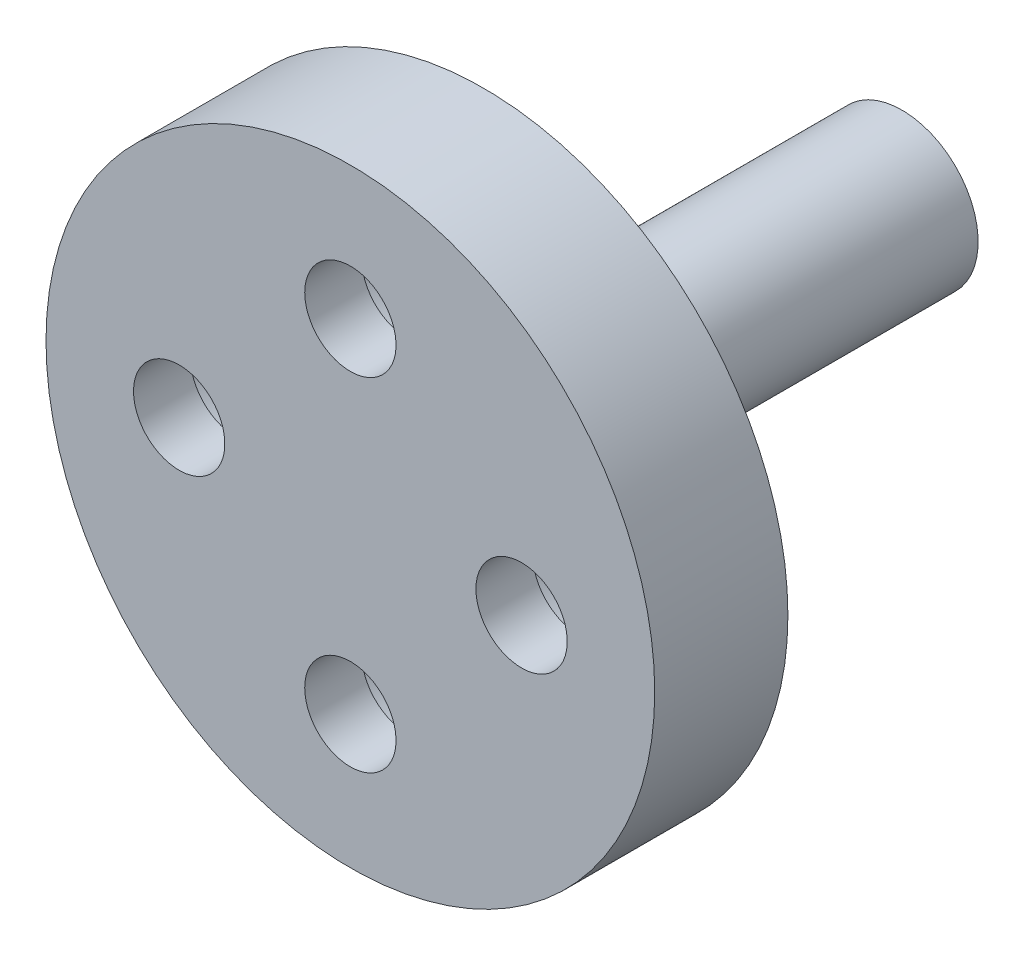
SolidWorks part; units mm, degrees
ref_plane "Front Plane" through (0, 0, 0) normal (0, 0, 1) x (1, 0, 0)
ref_plane "Top Plane" through (0, 0, 0) normal (0, 1, 0) x (1, 0, 0)
ref_plane "Right Plane" through (0, 0, 0) normal (1, 0, 0) x (0, 0, -1)
sketch "Sketch2" plane through (0, 0, 0) normal (0, 1, 0) x (1, 0, 0)
  line L0 (0, 0) -> (8, 0)
  line L1 (8, 0) -> (8, 3.5)
  line L2 (8, 3.5) -> (2, 3.5)
  line L3 (2, 3.5) -> (2, 14.5)
  line L4 (2, 14.5) -> (0, 14.5)
  line L5 (0, 14.5) -> (0, 0)
  dimension "D1" = 8
  dimension "D2" = 14.5
  dimension "D3" = 11
  dimension "D4" = 2
revolve "Revolve1" add sketch "Sketch2" angle 360 about L5
sketch "Sketch3" plane through (0, 0, -3.5) normal (0, 0, -1) x (-1, 0, 0)
  circle A0 centre (0, 0) radius 4.5
  dimension "D1" = 9
hole_wizard "CBORE for M2 SHCS1" positions "Sketch4" profile "Sketch5" counterbore size "M2" standard "ANSI Metric" end condition through all
sketch "Sketch4" plane through (0, 0, -3.5) normal (0, 0, -1) x (-1, 0, 0)
  circle A0 centre (0, 0) radius 4.5 construction
  point P0 (0, 4.5)
  point P4 (4.5, 0)
  point P6 (0, -4.5)
  point P8 (-4.5, 0)
sketch "Sketch5" plane through (0, 4.5, -3.5) normal (1, 0, 0) x (0, 1, 0)
  line L0 (0, 0) -> (0, 3.5)
  line L1 (0, 3.5) -> (1.2, 3.5)
  line L3 (1.2, 3.5) -> (1.2, 2)
  line L4 (2.2, 2) -> (1.2, 2)
  line L5 (2.2, 2) -> (2.2, 0.021)
  line L6 (2.2, 0.021) -> (2.225, 0)
  line L7 (2.225, 0) -> (0, 0)
  line L8 (-2.2, 0.021) -> (-2.225, 0) construction
  line L11 (0, -6.35) -> (0, 107.95) construction
  dimension "Thru Hole Dia." = 2.4
  dimension "Thru Hole Depth" = 3.5
  dimension "C'Bore Dia." = 4.4
  dimension "C'Bore Depth" = 2
  dimension "Near C'Sink Dia." = 4.45
  dimension "Near C'Sink Angle" = 100
